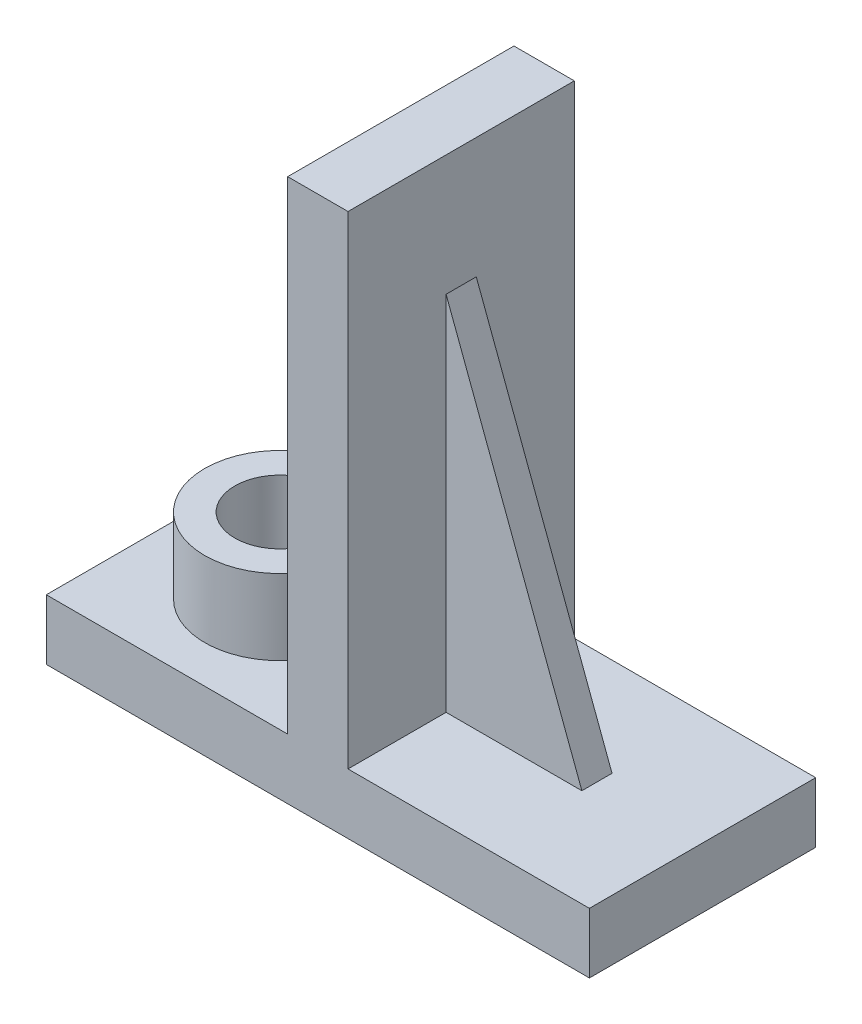
SolidWorks part; units mm, degrees
ref_plane "Front Plane" through (0, 0, 0) normal (0, 0, 1) x (1, 0, 0)
ref_plane "Top Plane" through (0, 0, 0) normal (0, 1, 0) x (1, 0, 0)
ref_plane "Right Plane" through (0, 0, 0) normal (1, 0, 0) x (0, 0, -1)
sketch "Sketch1" plane through (0, 0, 0) normal (0, 0, 1) x (1, 0, 0)
  line L0 (36, 0) -> (-36, 0)
  line L1 (-4, 72) -> (4, 72)
  line L2 (4, 8) -> (4, 72)
  line L3 (-4, 8) -> (-4, 72)
  line L4 (36, 8) -> (4, 8)
  line L5 (-36, 8) -> (-36, 0)
  line L6 (36, 8) -> (36, 0)
  line L10 (-4, 8) -> (-36, 8)
  line L11 (36, 8) -> (-36, 8) construction
  point P4 (0, 0)
  dimension "D1" = 72
  dimension "D2" = 72
  dimension "D3" = 8
  dimension "D5" = 64
  dimension "D6" = 32
  dimension "D4" = 8
extrude "Boss-Extrude1" add sketch "Sketch1" along normal mid plane 30
sketch "Sketch2" plane through (0, 0, 0) normal (0, 0, 1) x (1, 0, 0)
  line L0 (4, 8) -> (4, 56)
  line L1 (4, 8) -> (4, 72) construction
  line L2 (4, 56) -> (22, 8)
  line L3 (36, 8) -> (4, 8) construction
  line L4 (22, 8) -> (4, 8)
  line L5 (36, 0) -> (36, 8) construction
  dimension "D1" = 48
  dimension "D2" = 14
extrude "Boss-Extrude2" add sketch "Sketch2" along normal mid plane 4
sketch "Sketch3" plane through (0, 8, 0) normal (0, 1, 0) x (1, 0, 0)
  circle A0 centre (-20, 0) radius 10
  circle A1 centre (-20, 0) radius 6
  dimension "D1" = 20
  dimension "D2" = 12
extrude "Boss-Extrude3" add sketch "Sketch3" along normal blind 10
sketch "Sketch4" plane through (0, 0, 0) normal (0, -1, 0) x (1, 0, 0)
  circle A1 centre (-20, 0) radius 6
  circle A2 centre (-20, 0) radius 6
  dimension "D1" = 0
extrude "Cut-Extrude1" cut sketch "Sketch4" against normal blind 10
